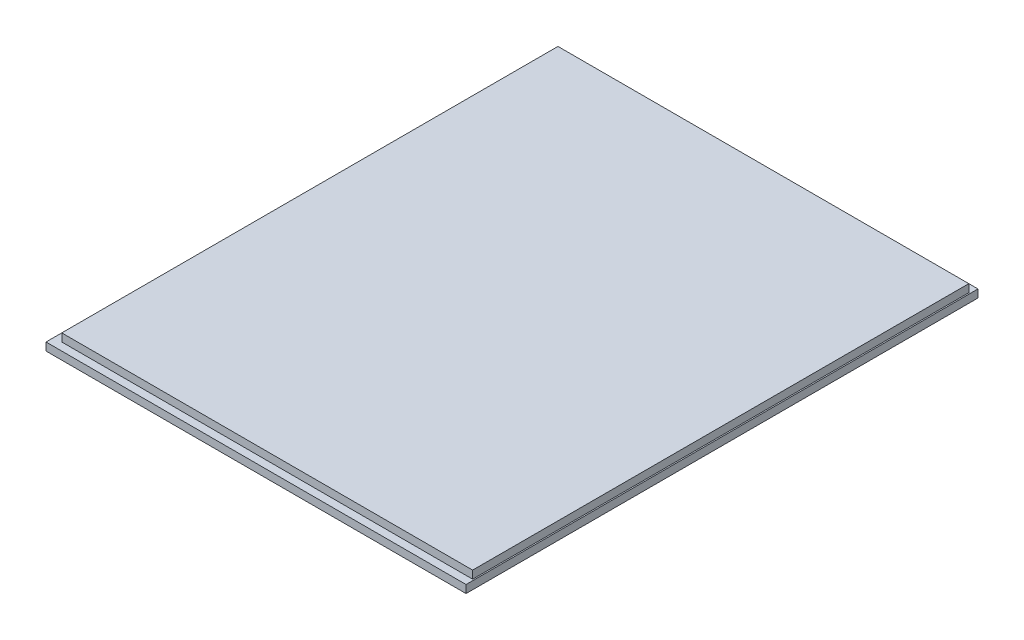
SolidWorks part; units mm, degrees
material "Custom Plastic"
ref_plane "Front" through (0, 0, 0) normal (0, 0, 1) x (1, 0, 0)
ref_plane "Top" through (0, 0, 0) normal (0, 1, 0) x (1, 0, 0)
ref_plane "Right" through (0, 0, 0) normal (1, 0, 0) x (0, 0, -1)
sketch "Sketch1" plane through (0, 0, 0) normal (0, 1, 0) x (1, 0, 0)
  line L0 (-103.1875, 123.825) -> (-103.1875, -123.825) construction
  line L1 (-103.1875, 123.825) -> (100.0125, 123.825)
  line L2 (-103.1875, 123.825) -> (-103.1875, -123.825)
  line L3 (-103.1875, -123.825) -> (100.0125, -123.825)
  line L4 (100.0125, 123.825) -> (100.0125, -123.825)
  line L5 (-103.1875, 123.825) -> (100.0125, -123.825) construction
  line L6 (-103.1875, -123.825) -> (100.0125, 123.825) construction
  line L7 (-103.1875, -123.825) -> (100.0125, -123.825) construction
  point P0 (0, 0)
extrude "Boss-Extrude1" add sketch "Sketch1" along normal blind 3.81
sketch "Sketch2" plane through (0, 3.81, 0) normal (0, 1, 0) x (1, 0, 0)
  line L0 (-103.1875, -123.825) -> (100.0125, -123.825) construction
  line L1 (-99.3775, -120.015) -> (99.3775, -120.015)
  line L2 (-99.3775, -120.015) -> (-99.3775, 120.015)
  line L3 (-99.3775, 120.015) -> (99.3775, 120.015)
  line L4 (99.3775, -120.015) -> (99.3775, 120.015)
  line L5 (-99.3775, -120.015) -> (99.3775, 120.015) construction
  line L6 (-99.3775, 120.015) -> (99.3775, -120.015) construction
  line L7 (-103.1875, 123.825) -> (-103.1875, -123.825) construction
  point P0 (0, 0)
  dimension "D1" = 3.81
  dimension "D2" = 3.81
extrude "Boss-Extrude2" add sketch "Sketch2" along normal blind 3.81
sketch "Sketch3" plane through (0, 0, 0) normal (0, -1, 0) x (1, 0, 0)
  line L0 (100.0125, 123.825) -> (100.0125, -123.825) construction
  line L1 (96.2025, -120.015) -> (-96.2025, -120.015)
  line L2 (96.2025, -120.015) -> (96.2025, 120.015)
  line L3 (96.2025, 120.015) -> (-96.2025, 120.015)
  line L4 (-96.2025, -120.015) -> (-96.2025, 120.015)
  line L5 (96.2025, -120.015) -> (-96.2025, 120.015) construction
  line L6 (96.2025, 120.015) -> (-96.2025, -120.015) construction
  line L7 (100.0125, -123.825) -> (-103.1875, -123.825) construction
  line L9 (94.1665, -117.475) -> (-94.1665, -117.475)
  line L10 (94.1665, -117.475) -> (94.1665, 117.475)
  line L11 (94.1665, 117.475) -> (-94.1665, 117.475)
  line L12 (-94.1665, -117.475) -> (-94.1665, 117.475)
  line L13 (94.1665, -117.475) -> (-94.1665, 117.475) construction
  line L14 (94.1665, 117.475) -> (-94.1665, -117.475) construction
  point P0 (0, 0)
  point P10 (0, 0)
  dimension "D1" = 3.81
  dimension "D2" = 3.81
  dimension "D3" = 2.54
extrude "Boss-Extrude3" add sketch "Sketch3" along normal blind 3.81
sketch "Sketch4" plane through (0, 0, 0) normal (0, -1, 0) x (-1, 0, 0)
  line L0 (-94.1665, 117.475) -> (94.1665, -117.475) construction
  line L1 (94.1665, 117.475) -> (-94.1665, -117.475) construction
  line L2 (-92.5388, 117.475) -> (-19.4474, 26.2917)
  line L3 (94.1665, 117.475) -> (-94.1665, 117.475) construction
  line L4 (94.1665, -117.475) -> (94.1665, 117.475) construction
  line L5 (92.5388, -117.475) -> (19.4474, -26.2917)
  line L6 (-94.1665, -117.475) -> (94.1665, -117.475) construction
  line L7 (-94.1665, 117.475) -> (-94.1665, -117.475) construction
  line L8 (-94.1665, 115.4445) -> (-94.1665, 117.475)
  line L9 (-94.1665, 117.475) -> (-92.5388, 117.475)
  line L10 (94.1665, -115.4445) -> (94.1665, -117.475)
  line L11 (94.1665, -117.475) -> (92.5388, -117.475)
  line L12 (21.4293, -24.703) -> (94.1665, -115.4445)
  line L13 (-21.4293, 24.703) -> (-94.1665, 115.4445)
  line L14 (-92.5388, -117.475) -> (-94.1665, -117.475)
  line L15 (-94.1665, -117.475) -> (-94.1665, -115.4445)
  line L16 (-94.1665, -115.4445) -> (-21.4293, -24.703)
  line L17 (92.5388, 117.475) -> (94.1665, 117.475)
  line L18 (94.1665, 117.475) -> (94.1665, 115.4445)
  line L19 (94.1665, 115.4445) -> (21.4293, 24.703)
  line L20 (-19.4474, -26.2917) -> (-92.5388, -117.475)
  line L21 (19.4474, 26.2917) -> (92.5388, 117.475)
  circle A0 centre (0, 0) radius 30.1625
  arc A1 (-19.4474, -26.2917) -> (19.4474, -26.2917) centre (0, 0) ccw
  arc A2 (21.4293, -24.703) -> (21.4293, 24.703) centre (0, 0) ccw
  arc A3 (19.4474, 26.2917) -> (-19.4474, 26.2917) centre (0, 0) ccw
  arc A4 (-21.4293, 24.703) -> (-21.4293, -24.703) centre (0, 0) ccw
  dimension "D1" = 60.325
  dimension "D2" = 65.405
  dimension "D3" = 2.54
  dimension "D4" = 1.27
  dimension "D5" = 1.27
  dimension "D6" = 2.54
extrude "Boss-Extrude4" add sketch "Sketch4" along normal up to surface (3.81 mm away) up to face at (0, -3.81, 0)
